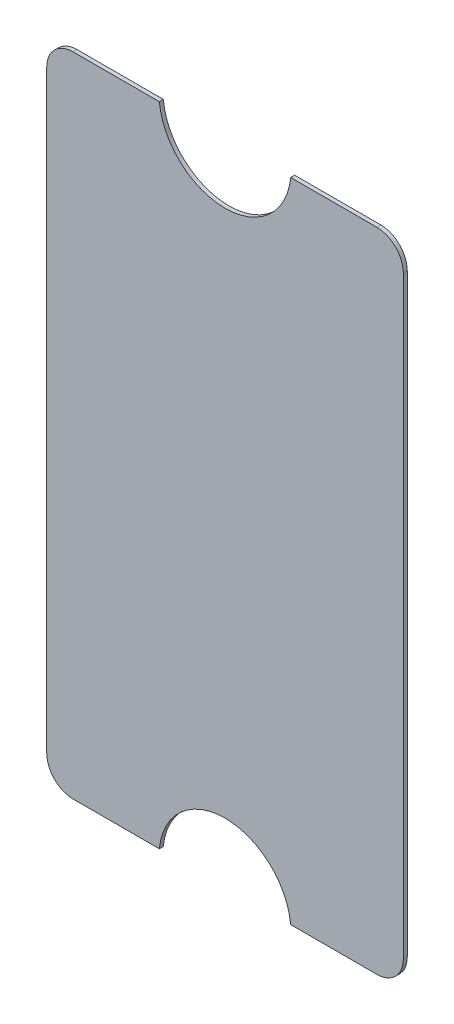
SolidWorks part; units mm, degrees
material "Медь"
ref_plane "Спереди" through (0, 0, 0) normal (0, 0, 1) x (1, 0, 0)
ref_plane "Сверху" through (0, 0, 0) normal (0, 1, 0) x (1, 0, 0)
ref_plane "Справа" through (0, 0, 0) normal (1, 0, 0) x (0, 0, -1)
sketch "Эскиз1" plane through (0, 0, 0) normal (0, 0, 1) x (-1, 0, 0)
  line L12 (-4.3739, -0.5) -> (-10.8989, -0.5)
  line L13 (-12.8989, -2.5) -> (-12.8989, -47.5)
  line L14 (-10.8989, -49.5) -> (-4.3739, -49.5)
  line L15 (5.576, -49.5) -> (12.1011, -49.5)
  line L16 (14.1011, -47.5) -> (14.1011, -2.5)
  line L17 (12.1011, -0.5) -> (5.576, -0.5)
  arc A12 (-10.8989, -0.5) -> (-12.8989, -2.5) centre (-10.8989, -2.5) ccw
  arc A13 (-12.8989, -47.5) -> (-10.8989, -49.5) centre (-10.8989, -47.5) ccw
  arc A14 (5.576, -49.5) -> (-4.3739, -49.5) centre (0.6011, -50) ccw
  arc A15 (12.1011, -49.5) -> (14.1011, -47.5) centre (12.1011, -47.5) ccw
  arc A16 (14.1011, -2.5) -> (12.1011, -0.5) centre (12.1011, -2.5) ccw
  arc A17 (-4.3739, -0.5) -> (5.576, -0.5) centre (0.6011, 0) ccw
extrude "Бобышка-Вытянуть1" add sketch "Эскиз1" along normal blind 0.3
